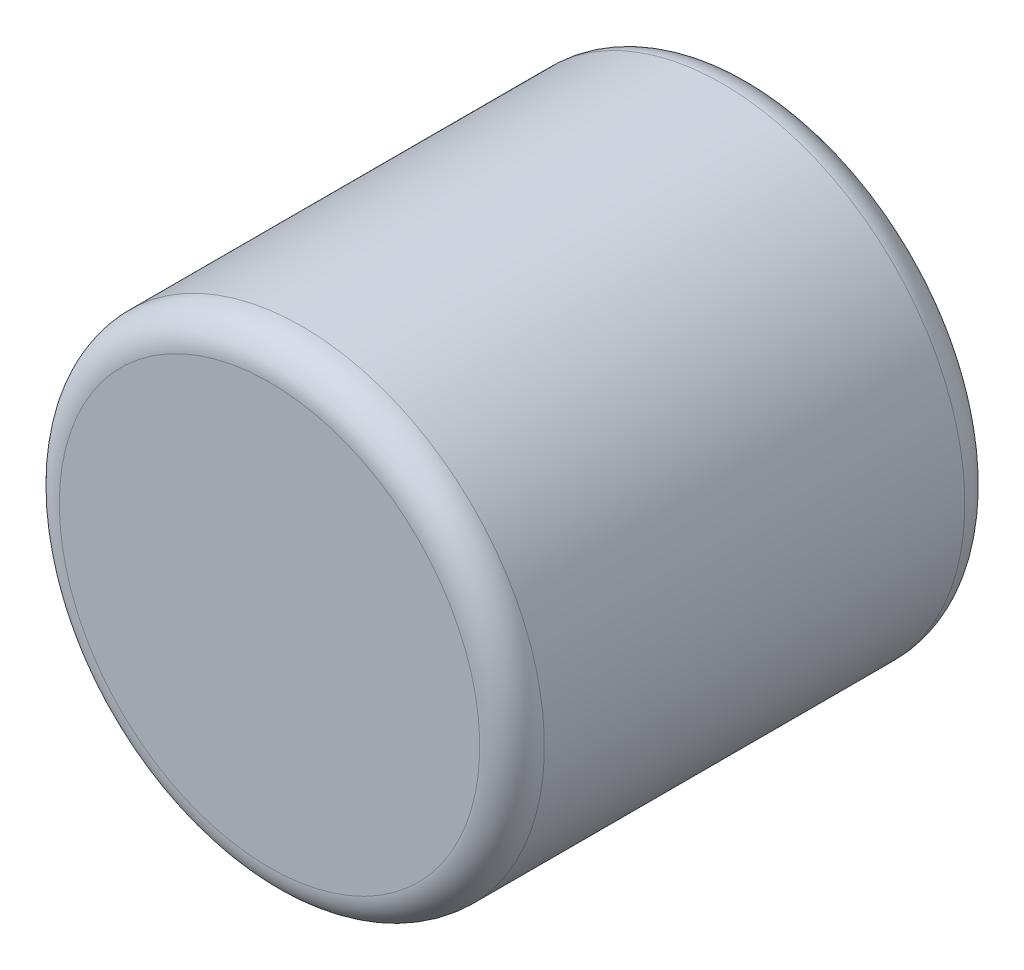
SolidWorks part; units mm, degrees
ref_plane "Front" through (0, 0, 0) normal (0, 0, 1) x (1, 0, 0)
ref_plane "Top" through (0, 0, 0) normal (0, 1, 0) x (1, 0, 0)
ref_plane "Right" through (0, 0, 0) normal (1, 0, 0) x (0, 0, -1)
sketch "Эскиз2" plane through (0, 0, 0) normal (1, 0, 0) x (0, 0, -1)
  line L0 (0, 0) -> (-9.8044, 0) construction
  line L1 (0, 0) -> (-3, 0)
  line L2 (0, 0) -> (0, -1.3)
  line L3 (-0.2, -1.5) -> (-2.8, -1.5)
  line L4 (-3, -1.3) -> (-3, 0)
  arc A0 (0, -1.3) -> (-0.2, -1.5) centre (-0.2, -1.3) cw
  arc A1 (-2.8, -1.5) -> (-3, -1.3) centre (-2.8, -1.3) cw
  dimension "D1" = 3
  dimension "D3" = 0.2
  dimension "D2" = 3
revolve "Повернуть1" add sketch "Эскиз2" angle 360 about L0
